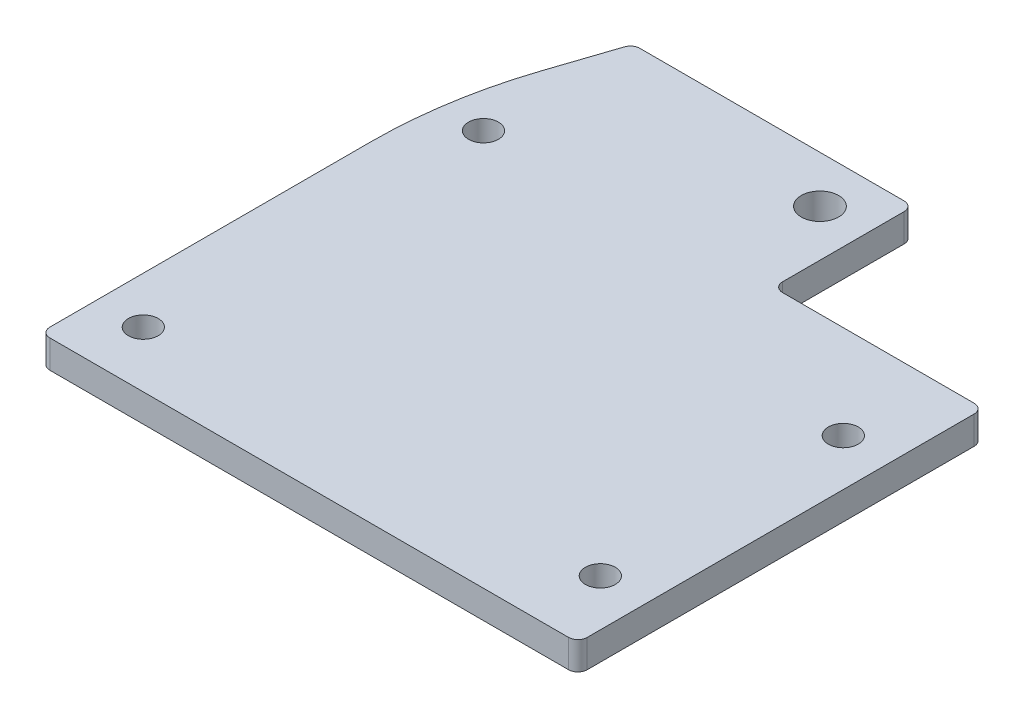
SolidWorks part; units mm, degrees
material "5052-H34"
ref_plane "正面" through (0, 0, 0) normal (0, 0, 1) x (1, 0, 0)
ref_plane "平面" through (0, 0, 0) normal (0, 1, 0) x (1, 0, 0)
ref_plane "右側面" through (0, 0, 0) normal (1, 0, 0) x (0, 0, -1)
sketch "ｽｹｯﾁ1" plane through (0, 0, 0) normal (0, 1, 0) x (1, 0, 0)
  line L0 (0, 58.4) -> (35, 58.4)
  line L1 (0, 0) -> (57.5, 0)
  line L2 (0, 0) -> (0, 58.4)
  line L4 (57.5, 0) -> (57.5, 43.4)
  line L5 (35, 58.4) -> (35, 43.4)
  line L6 (35, 43.4) -> (57.5, 43.4)
  line L7 (0, 29.2) -> (57.5, 29.2) construction
  circle A0 centre (52.5, 7.4) radius 1.6
  circle A1 centre (52.5, 33.4) radius 1.6
  circle A2 centre (30, 53.4) radius 2
  circle A3 centre (5, 42.4) radius 1.6
  circle A4 centre (5, 6) radius 1.6
  point P19 (0, 0)
  point P20 (0, 0)
  dimension "D4" = 33.4
  dimension "D5" = 3.2
  dimension "D9" = 4
  dimension "D10" = 5
  dimension "D11" = 5
  dimension "D12" = 3.2
  dimension "D13" = 5
  dimension "D14" = 16
  dimension "D15" = 6
  dimension "D1" = 43.4
  dimension "D2" = 57.5
  dimension "D3" = 7.4
  dimension "D6" = 5
  dimension "D7" = 35
  dimension "D8" = 58.4
extrude "ﾎﾞｽ - 押し出し1" add sketch "ｽｹｯﾁ1" along normal blind 3
sketch "ｽｹｯﾁ2" plane through (0, 3, 0) normal (0, 1, 0) x (1, 0, 0)
  line L0 (5, 58.4) -> (0, 58.4)
  line L1 (35, 58.4) -> (0, 58.4) construction
  line L2 (0, 58.4) -> (0, 43.4)
  line L3 (0, 58.4) -> (0, 0) construction
  line L4 (0, 43.4) -> (5, 58.4)
  dimension "D1" = 5
  dimension "D2" = 15
extrude "ｶｯﾄ - 押し出し1" cut sketch "ｽｹｯﾁ2" against normal up to surface (3 mm away) up to face at (5, 0, -40.8)
fillet "ﾌｨﾚｯﾄ1" radius 50 1 edges at (0, 1.5, -43.4)
fillet "ﾌｨﾚｯﾄ2" radius 1 6 edges at (0, 1.5, 0) (57.5, 1.5, 0) (57.5, 1.5, -43.4) (35, 1.5, -43.4) (35, 1.5, -58.4) (5, 1.5, -58.4)
